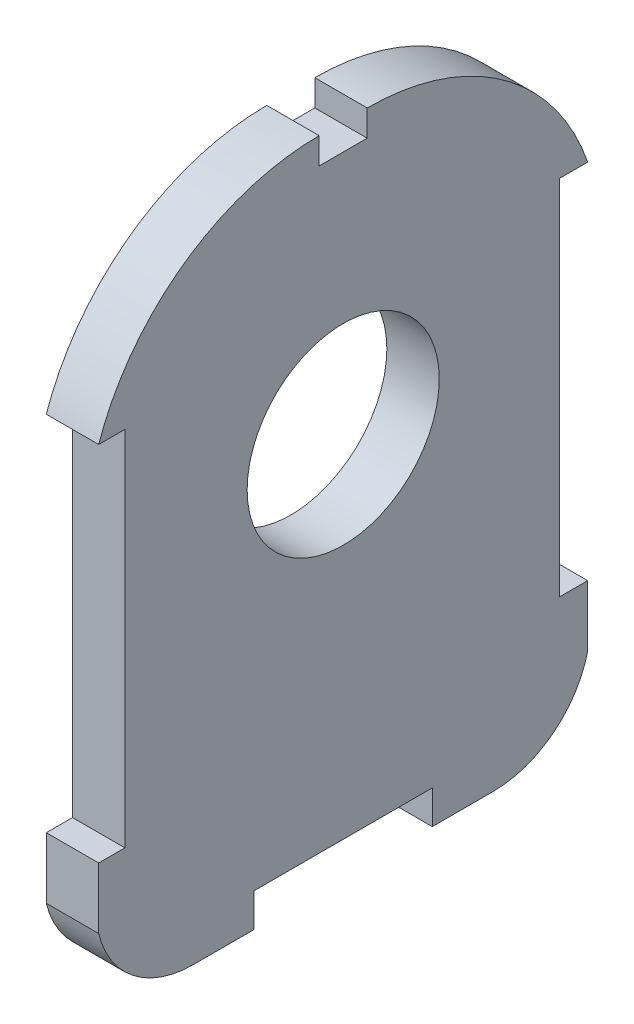
SolidWorks part; units mm, degrees
ref_plane "Front Plane" through (0, 0, 0) normal (0, 0, 1) x (1, 0, 0)
ref_plane "Top Plane" through (0, 0, 0) normal (0, 1, 0) x (1, 0, 0)
ref_plane "Right Plane" through (0, 0, 0) normal (1, 0, 0) x (0, 0, -1)
sketch "Sketch1" plane through (0, 0, 0) normal (1, 0, 0) x (0, 0, -1)
  line L0 (-10.2, 0) -> (10.2, 0)
  line L1 (10.2, 0) -> (10.2, -3)
  line L2 (0, 0) -> (0, 30) construction
  line L3 (0, 52) -> (0, 69) construction
  line L4 (-2.75, 69) -> (2.75, 69)
  line L5 (2.75, 69) -> (2.75, 72)
  line L6 (-28.5, 52) -> (28.5, 52) construction
  line L7 (11, 41) -> (25, 41) construction
  line L8 (25, 41) -> (25, 54)
  line L9 (25, 54) -> (28, 54)
  line L10 (25, 54) -> (25, 12.5)
  line L11 (25, 12.5) -> (28, 12.5)
  line L12 (10.2, -3) -> (17.2, -3)
  line L13 (28, 12.5) -> (28, 5.5)
  line L14 (-2.75, 69) -> (-2.75, 72)
  line L15 (-10.2, 0) -> (-10.2, -3)
  line L16 (-10.2, -3) -> (-17.2, -3)
  line L17 (-28, 12.5) -> (-28, 5.5)
  line L18 (-25, 12.5) -> (-28, 12.5)
  line L19 (-25, 54) -> (-25, 12.5)
  line L20 (-25, 54) -> (-28, 54)
  line L21 (-25, 41) -> (-25, 54)
  circle A0 centre (0, 41) radius 11
  arc A1 (17.2, -3) -> (28, 5.5) centre (17.2, 8.1112) ccw
  arc A2 (2.75, 72) -> (28, 54) centre (2.75, 45.2899) cw
  arc A3 (-17.2, -3) -> (-28, 5.5) centre (-17.2, 8.1112) cw
  arc A4 (-2.75, 72) -> (-28, 54) centre (-2.75, 45.2899) ccw
  point P4 (0, 0)
  point P15 (0, 69)
  point P19 (0, 52)
  dimension "D3" = 22
  dimension "D1" = 20.4
  dimension "D2" = 3
  dimension "D4" = 17
  dimension "D5" = 5.5
  dimension "D6" = 30
  dimension "D7" = 3
  dimension "D8" = 57
  dimension "D9" = 14
  dimension "D10" = 3
  dimension "D11" = 13
  dimension "D12" = 41.5
  dimension "D13" = 3
  dimension "D14" = 7
  dimension "D15" = 7
extrude "Boss-Extrude1" add sketch "Sketch1" along normal blind 6 contours L14 A4 L20 L19 L18 L17 A3 L16 L15 L0 L1 L12 A1 L13 L11 L10 L8 L9 A2 L5 L4 A0
sketch "Sketch5" plane through (0, 54, 0) normal (0, -1, 0) x (1, 0, 0)
  line L0 (0, -25) -> (6, -25)
  line L3 (6, -25) -> (6, -24.7517)
  line L4 (6, -24.7517) -> (0, -25)
  dimension "D1" = 2.37
extrude "Cut-Extrude3" cut sketch "Sketch5" along normal up to surface (41.5 mm away) up to face at (3, 12.5, -26.5)
sketch "Sketch6" plane through (0, 0, -10.2) normal (0, 0, 1) x (1, 0, 0)
  line L0 (0, 0) -> (6, 0)
  line L3 (0, 0) -> (6, 0.8432)
  line L4 (6, -3) -> (6, 5.5) construction
  line L5 (6, 0.8432) -> (6, 0)
  dimension "D1" = 8
extrude "Cut-Extrude5" cut sketch "Sketch6" along normal up to surface (20.4 mm away) up to face at (3, -1.5, 10.2)
